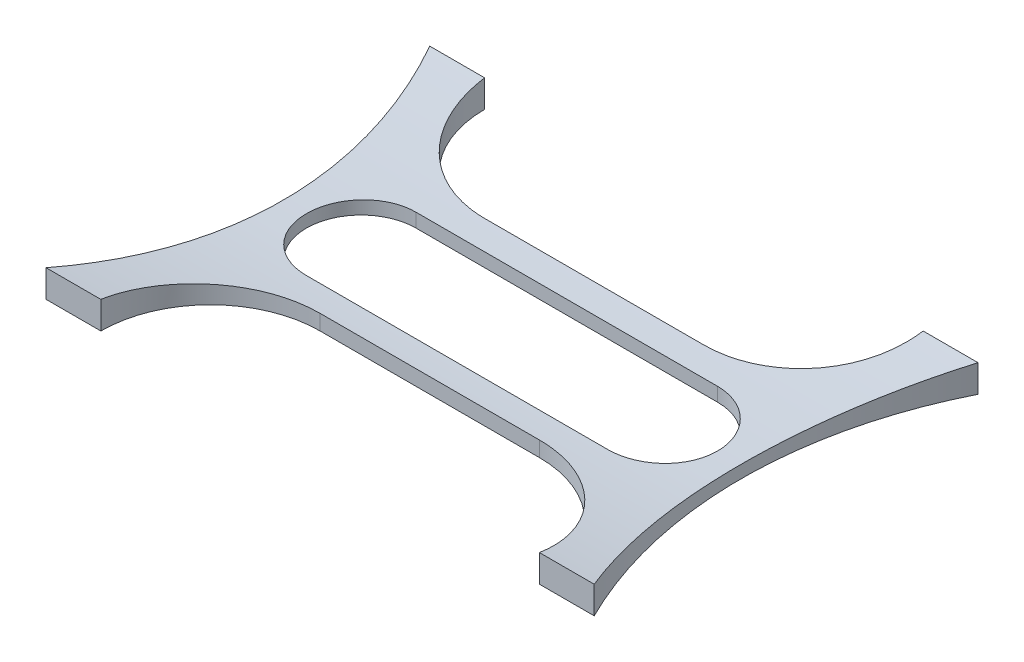
SolidWorks part; units mm, degrees
ref_plane "Plan de face" through (0, 0, 0) normal (0, 0, 1) x (1, 0, 0)
ref_plane "Plan de dessus" through (0, 0, 0) normal (0, 1, 0) x (1, 0, 0)
ref_plane "Plan de droite" through (0, 0, 0) normal (1, 0, 0) x (0, 0, -1)
sketch "Esquisse1" plane through (0, 0, 0) normal (0, 1, 0) x (1, 0, 0)
  line L0 (-180.4082, 0) -> (187.3469, 0) construction
  line L1 (100, 70) -> (-100, 70) construction
  line L2 (100, 70) -> (100, -70) construction
  line L3 (100, -70) -> (-100, -70) construction
  line L4 (-100, 70) -> (-100, -70) construction
  line L5 (100, 70) -> (-100, -70) construction
  line L6 (100, -70) -> (-100, 70) construction
  line L7 (0, 70) -> (0, -70) construction
  line L8 (-100, 70) -> (-80, 70)
  line L9 (-100, 30) -> (100, 30) construction
  line L10 (55, 0) -> (-55, 0) construction
  line L11 (55, -20) -> (-55, -20)
  line L12 (55, 20) -> (-55, 20)
  line L13 (-40, 30) -> (40, 30)
  line L14 (62.5, -15) -> (-62.5, -15) construction
  line L15 (62.5, -15) -> (62.5, 15) construction
  line L16 (62.5, 15) -> (-62.5, 15) construction
  line L17 (-62.5, -15) -> (-62.5, 15) construction
  line L18 (62.5, -15) -> (-62.5, 15) construction
  line L19 (62.5, 15) -> (-62.5, -15) construction
  line L20 (-40, -30) -> (40, -30)
  line L21 (-100, -70) -> (-80, -70)
  line L22 (100, -70) -> (80, -70)
  line L23 (100, 70) -> (80, 70)
  arc A0 (-100, 70) -> (-100, -70) centre (-240, 0) cw
  arc A1 (55, -20) -> (55, 20) centre (55, 0) ccw
  arc A2 (-55, 20) -> (-55, -20) centre (-55, 0) ccw
  arc A3 (-80, 70) -> (-40, 30) centre (-40, 70) ccw
  arc A4 (-80, -70) -> (-40, -30) centre (-40, -70) cw
  arc A5 (80, -70) -> (40, -30) centre (40, -70) ccw
  arc A6 (100, 70) -> (100, -70) centre (240, 0) ccw
  arc A7 (80, 70) -> (40, 30) centre (40, 70) cw
  point P0 (0, 0)
  point P17 (0, 0)
  point P22 (0, 0)
  point P30 (0, -30)
  point P38 (0, 30)
  dimension "D3" = 140
  dimension "D9" = 40
  dimension "D1" = 200
  dimension "D2" = 140
  dimension "D4" = 110
  dimension "D5" = 40
  dimension "D6" = 30
  dimension "D7" = 125
  dimension "D8" = 10
  dimension "D10" = 20
extrude "Boss.-Extru.1" add sketch "Esquisse1" along normal blind 10
sketch "Esquisse2" plane through (0, 0, 0) normal (1, 0, 0) x (0, 0, -1)
  line L0 (0, 44.8718) -> (0, -36.4202) construction
  line L4 (-70, 0) -> (70, 0)
  line L5 (70, 0) -> (70, 10)
  line L6 (70, 10) -> (-70, 10)
  line L7 (-70, 10) -> (-70, 0)
  line L8 (-70, 0) -> (70, 0)
  line L9 (70, 0) -> (70, 10)
  line L10 (70, 10) -> (-70, 10)
  line L11 (-70, 10) -> (-70, 0)
  arc A0 (-70, 10) -> (70, 10) centre (0, 460) ccw
  dimension "D2" = 450
  dimension "D1" = 0
extrude "Enlèv. mat.-Extru.1" cut sketch "Esquisse2" against normal through all both and the other way through all contours L0 L10 A0 | L10 L0 A0
